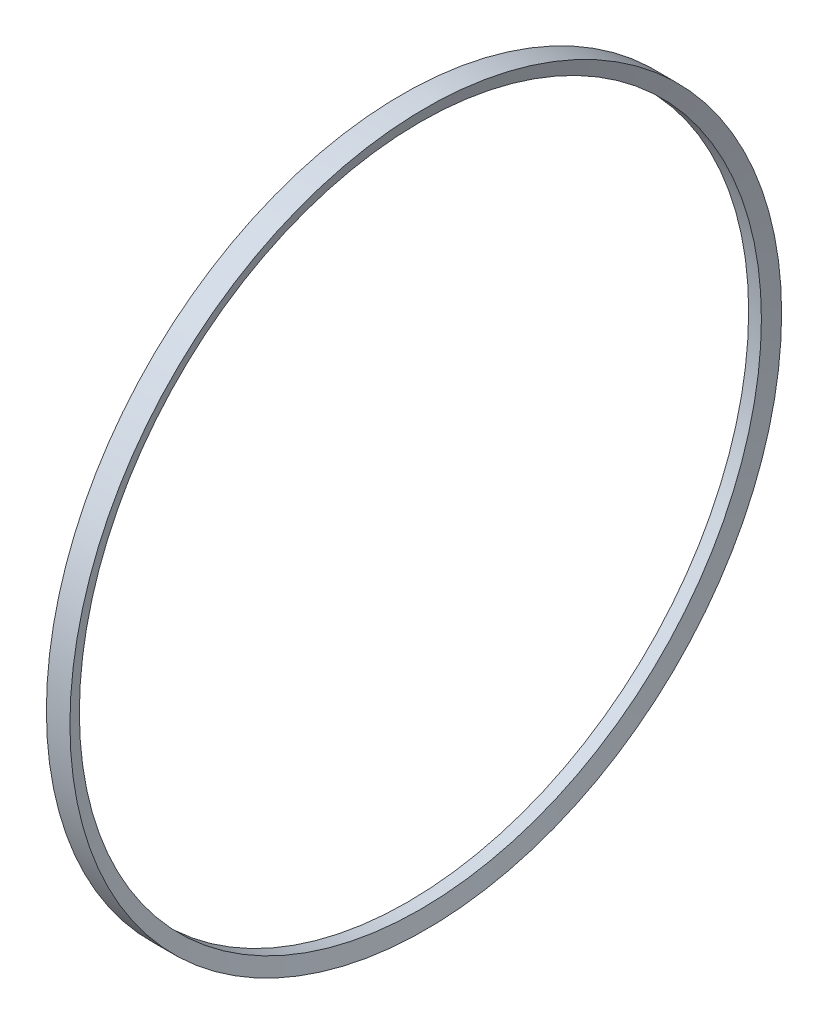
SolidWorks part; units mm, degrees
ref_plane "Front" through (0, 0, 0) normal (0, 0, 1) x (1, 0, 0)
ref_plane "Top" through (0, 0, 0) normal (0, 1, 0) x (1, 0, 0)
ref_plane "Right" through (0, 0, 0) normal (1, 0, 0) x (0, 0, -1)
sketch "Sketch1" plane through (0, 0, 0) normal (0, 0, 1) x (1, 0, 0)
  line L0 (0, 0) -> (345.9229, 0) construction
  line L1 (0, 0) -> (0, 192) construction
  line L2 (-6.35, 192) -> (6.35, 192)
  line L3 (-3.4382, 184) -> (3.4382, 184)
  line L4 (-6.35, 192) -> (-3.4382, 184)
  line L5 (6.35, 192) -> (3.4382, 184)
  point P8 (0, 192)
  point P11 (0, 184)
  dimension "D1" = 192
  dimension "D2" = 12.7
  dimension "D4" = 20
revolve "Revolve1" add sketch "Sketch1" angle 360 about L0
